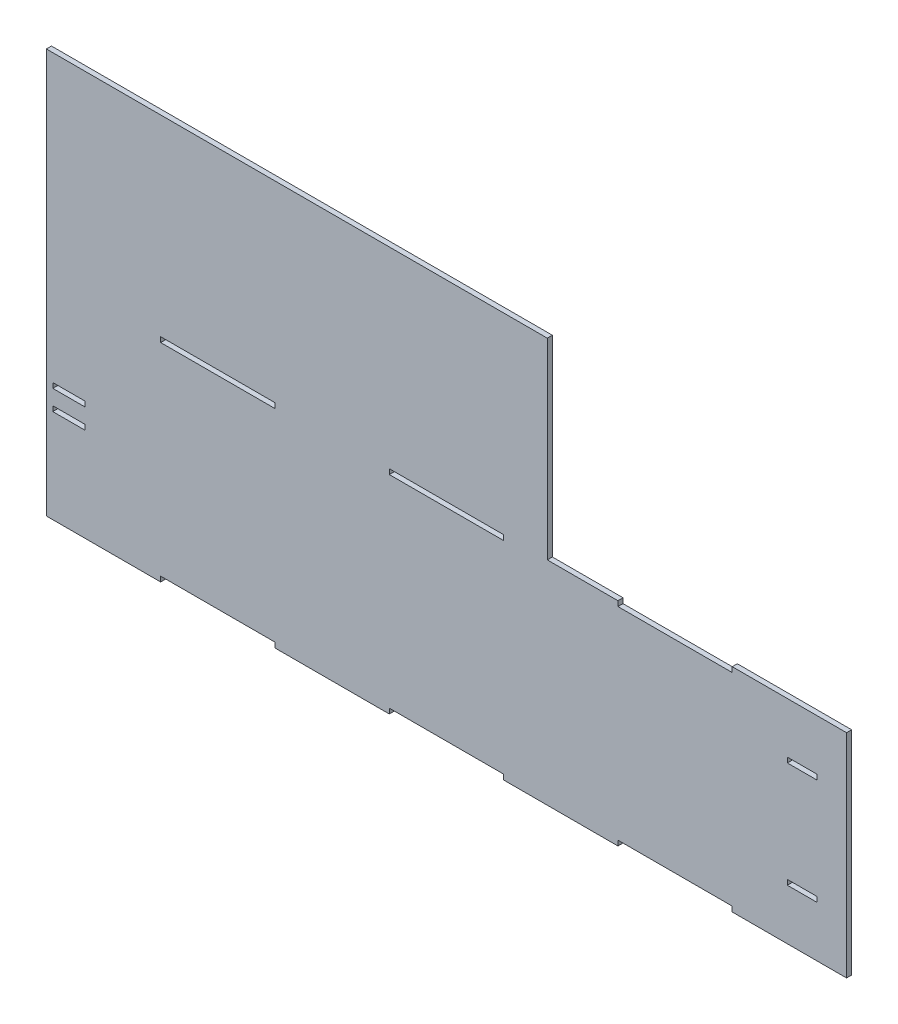
SolidWorks part; units mm, degrees
ref_plane "Front Plane" through (0, 0, 0) normal (0, 0, 1) x (1, 0, 0)
ref_plane "Top Plane" through (0, 0, 0) normal (0, 1, 0) x (1, 0, 0)
ref_plane "Right Plane" through (0, 0, 0) normal (1, 0, 0) x (0, 0, -1)
sketch "Sketch1" plane through (0, 0, 0) normal (0, 0, 1) x (1, 0, 0)
  line L1 (0, 0) -> (500, 0) construction
  line L2 (0, 0) -> (0, 132.75)
  line L4 (500, 0) -> (500, 132.75)
  line L5 (71.4286, 132.75) -> (71.4286, 129.575)
  line L6 (71.4286, 129.575) -> (142.8571, 129.575)
  line L7 (142.8571, 129.575) -> (142.8571, 132.75)
  line L9 (214.2857, 132.75) -> (214.2857, 129.575)
  line L10 (214.2857, 129.575) -> (285.7143, 129.575)
  line L11 (285.7143, 129.575) -> (285.7143, 132.75)
  line L13 (357.1429, 132.75) -> (357.1429, 129.575)
  line L14 (357.1429, 129.575) -> (428.5714, 129.575)
  line L15 (428.5714, 129.575) -> (428.5714, 132.75)
  line L17 (0, 66.375) -> (500, 66.375) construction
  line L18 (428.5714, 0) -> (500, 0)
  line L19 (428.5714, 3.175) -> (428.5714, 0)
  line L20 (357.1429, 3.175) -> (428.5714, 3.175)
  line L21 (357.1429, 0) -> (357.1429, 3.175)
  line L22 (285.7143, 0) -> (357.1429, 0)
  line L23 (285.7143, 3.175) -> (285.7143, 0)
  line L24 (214.2857, 3.175) -> (285.7143, 3.175)
  line L25 (214.2857, 0) -> (214.2857, 3.175)
  line L26 (142.8571, 0) -> (214.2857, 0)
  line L27 (142.8571, 3.175) -> (142.8571, 0)
  line L28 (71.4286, 3.175) -> (142.8571, 3.175)
  line L29 (71.4286, 0) -> (71.4286, 3.175)
  line L30 (0, 0) -> (71.4286, 0)
  line L31 (4, 61.675) -> (4, 66.375) construction
  line L32 (4, 61.675) -> (24, 61.675)
  line L33 (4, 61.675) -> (4, 58.5)
  line L34 (4, 58.5) -> (24, 58.5)
  line L35 (24, 61.675) -> (24, 58.5)
  line L36 (4, 71.075) -> (24, 71.075)
  line L37 (4, 71.075) -> (4, 74.25)
  line L38 (4, 74.25) -> (24, 74.25)
  line L39 (24, 71.075) -> (24, 74.25)
  line L40 (481.5, 66.375) -> (481.5, 97.875) construction
  line L41 (481.5, 34.875) -> (463, 34.875)
  line L42 (481.5, 97.875) -> (463, 97.875)
  line L43 (481.5, 97.875) -> (481.5, 101.05)
  line L44 (481.5, 101.05) -> (463, 101.05)
  line L45 (463, 97.875) -> (463, 101.05)
  line L46 (481.5, 34.875) -> (481.5, 31.7)
  line L47 (481.5, 31.7) -> (463, 31.7)
  line L48 (463, 34.875) -> (463, 31.7)
  line L51 (0, 252.75) -> (0, 132.75)
  line L53 (285.7143, 132.75) -> (214.2857, 132.75)
  line L54 (142.8571, 132.75) -> (71.4286, 132.75)
  line L55 (278.2222, 252.75) -> (313, 252.75) construction
  line L56 (278.2222, 252.75) -> (313, 252.75)
  line L57 (313, 252.75) -> (313, 228.115) construction
  line L58 (313, 252.75) -> (313, 228.115)
  line L59 (313, 228.115) -> (313, 132.75)
  line L60 (313, 132.75) -> (357.1429, 132.75)
  line L61 (428.5714, 132.75) -> (500, 132.75)
  line L62 (278.2222, 252.75) -> (0, 252.75)
  dimension "D1" = 500
  dimension "D2" = 132.75
  dimension "D3" = 3.175
  dimension "D4" = 9.4
  dimension "D5" = 3.175
  dimension "D6" = 20
  dimension "D7" = 4.7
  dimension "D8" = 4
  dimension "D9" = 31.5
  dimension "D10" = 18.5
  dimension "D11" = 18.5
  dimension "D12" = 3.175
extrude "Boss-Extrude1" add sketch "Sketch1" along normal blind 3.175
